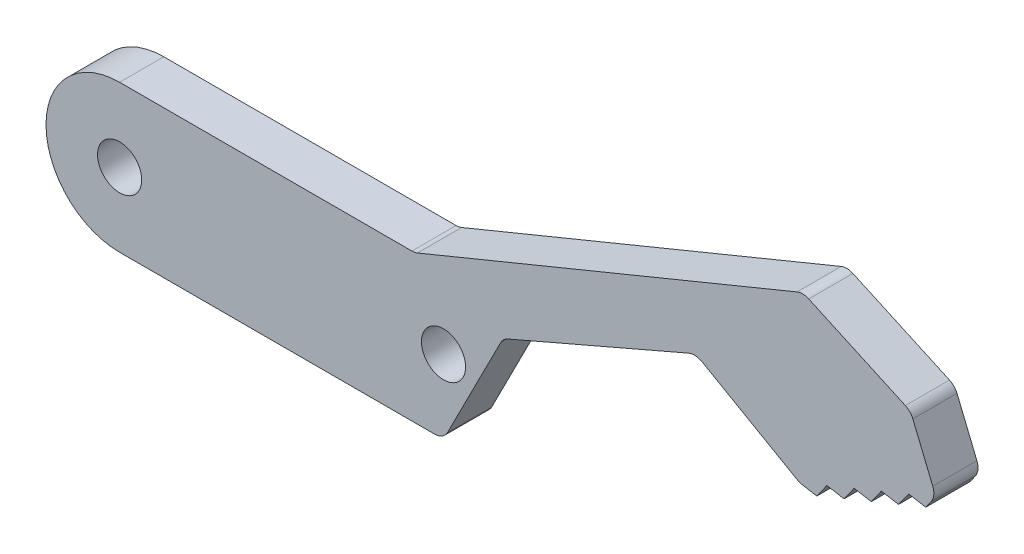
SolidWorks part; units mm, degrees
ref_plane "Front Plane" through (0, 0, 0) normal (0, 0, 1) x (1, 0, 0)
ref_plane "Top Plane" through (0, 0, 0) normal (0, 1, 0) x (1, 0, 0)
ref_plane "Right Plane" through (0, 0, 0) normal (1, 0, 0) x (0, 0, -1)
sketch "Sketch2" plane through (0, 0, 0) normal (0, 0, 1) x (1, 0, 0)
  line L0 (0, 0) -> (22, 0) construction
  line L1 (0, 5) -> (22, 5)
  line L2 (0, -5) -> (22, -5)
  line L3 (20.05, 5) -> (23.9914, -4.5863) construction
  line L4 (20.05, 5) -> (51.4959, 17.929) construction
  line L5 (23.9914, -4.5863) -> (55.4373, 8.3426) construction
  line L6 (51.4959, 17.929) -> (55.4373, 8.3426) construction
  line L7 (20.05, 5) -> (46.409, 15.8375)
  line L8 (46.409, 15.8375) -> (53.7261, 12.5046)
  line L9 (53.7261, 12.5046) -> (55.4373, 8.3426)
  line L10 (55.4373, 8.3426) -> (46.1885, 4.54) construction
  line L11 (46.1885, 4.54) -> (39.1141, 8.5908)
  line L12 (39.1141, 8.5908) -> (26.0419, 2.9433)
  line L13 (46.1885, 4.54) -> (47.3529, 4.3376)
  line L14 (47.3529, 4.3376) -> (48.0382, 5.3005)
  line L15 (47.3529, 4.3376) -> (54.752, 7.3797) construction
  line L16 (48.0382, 5.3005) -> (49.2027, 5.0981)
  line L17 (49.2027, 5.0981) -> (49.888, 6.0611)
  line L18 (49.888, 6.0611) -> (51.0524, 5.8587)
  line L19 (51.0524, 5.8587) -> (51.7378, 6.8216)
  line L20 (51.7378, 6.8216) -> (52.9022, 6.6192)
  line L21 (52.9022, 6.6192) -> (53.5875, 7.5821)
  line L22 (53.5875, 7.5821) -> (54.752, 7.3797)
  line L23 (54.752, 7.3797) -> (55.4373, 8.3426)
  line L24 (26.0419, 2.9433) -> (22, -5)
  arc A0 (0, 5) -> (0, -5) centre (0, 0) ccw
  arc A1 (22, -5) -> (22, 5) centre (22, 0) ccw
  circle A2 centre (22, 0) radius 1.5
  circle A3 centre (0, 0) radius 1.5
  point P3 (11, 0)
  dimension "D10" = 3
  dimension "D1" = 22
  dimension "D2" = 10
  dimension "D3" = 157.65
  dimension "D4" = 1.95
  dimension "D5" = 34
  dimension "D6" = 14.24
  dimension "D7" = 10
  dimension "D8" = 4.5
  dimension "D9" = 5.5
  dimension "D11" = 0.63
  dimension "D12" = 2
  dimension "D13" = 8
extrude "Boss-Extrude1" add sketch "Sketch2" along normal blind 3 contours A1 L1 A0 L2 A3 A2 | A1 L12 L11 L13 L14 L16 L17 L18 L19 L20 L21 L22 L23 L9 L8 L7 L1
fillet "Fillet1" radius 1 8 edges at (46.1885, 4.54, 1.5) (55.4373, 8.3426, 1.5) (53.7261, 12.5046, 1.5) (46.409, 15.8375, 1.5) (20.05, 5, 1.5) (39.1141, 8.5908, 1.5) (26.0419, 2.9433, 1.5) (22, -5, 1.5)
